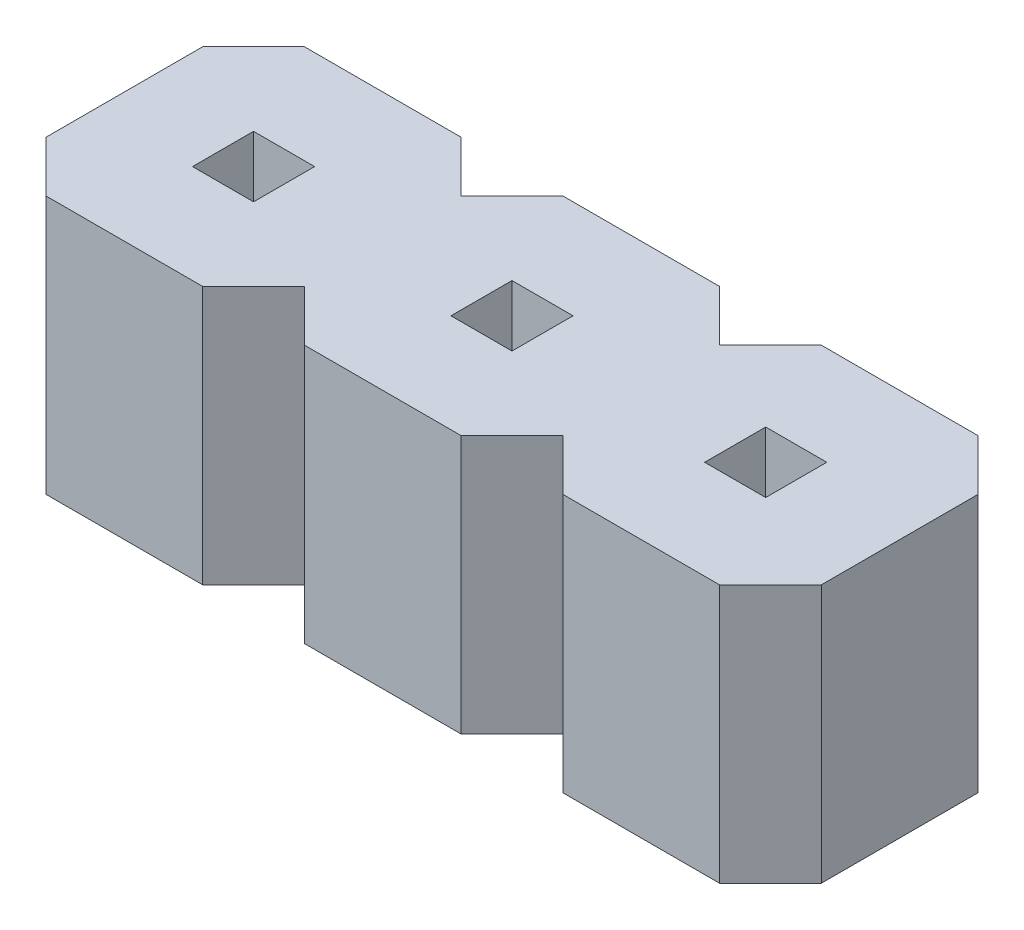
SolidWorks part; units mm, degrees
ref_plane "Спереди" through (0, 0, 0) normal (0, 0, 1) x (1, 0, 0)
ref_plane "Сверху" through (0, 0, 0) normal (0, 1, 0) x (1, 0, 0)
ref_plane "Справа" through (0, 0, 0) normal (1, 0, 0) x (0, 0, -1)
sketch "Sketch1" plane through (0, 0, 0) normal (0, 1, 0) x (1, 0, 0)
  line L0 (-5.08, 1.27) -> (0, 1.27) construction
  line L1 (-0.5, 0) -> (-2.04, 0)
  line L3 (-0.5, 2.54) -> (-2.04, 2.54)
  line L4 (-5.08, 0.5) -> (-5.08, 2.04)
  line L5 (-4.58, 2.54) -> (-5.08, 2.04)
  line L6 (-4.11, 0.97) -> (-3.51, 0.97)
  line L7 (-4.11, 0.97) -> (-4.11, 1.57)
  line L8 (-4.11, 1.57) -> (-3.51, 1.57)
  line L9 (-3.51, 0.97) -> (-3.51, 1.57)
  line L10 (-4.11, 0.97) -> (-3.51, 1.57) construction
  line L11 (-4.11, 1.57) -> (-3.51, 0.97) construction
  line L12 (-1.57, 0.97) -> (-0.97, 0.97)
  line L13 (-1.57, 0.97) -> (-1.57, 1.57)
  line L14 (-1.57, 1.57) -> (-0.97, 1.57)
  line L15 (-0.97, 0.97) -> (-0.97, 1.57)
  line L16 (-1.57, 0.97) -> (-0.97, 1.57) construction
  line L17 (-1.57, 1.57) -> (-0.97, 0.97) construction
  line L18 (-4.58, 0) -> (-5.08, 0.5)
  line L19 (0, 0.5) -> (-0.5, 0)
  line L20 (0, 2.04) -> (-0.5, 2.54)
  line L21 (-2.54, 2.54) -> (-2.54, 0) construction
  line L22 (-2.54, 0.5) -> (-2.04, 0)
  line L23 (-3.04, 2.54) -> (-2.54, 2.04)
  line L24 (-2.54, 2.04) -> (-2.04, 2.54)
  line L25 (-3.04, 0) -> (-2.54, 0.5)
  line L26 (-3.04, 2.54) -> (-4.58, 2.54)
  line L27 (-3.04, 0) -> (-4.58, 0)
  line L28 (0, 2.04) -> (0.5, 2.54)
  line L29 (0.5, 2.54) -> (2.04, 2.54)
  line L30 (2.04, 2.54) -> (2.54, 2.04)
  line L31 (2.54, 2.04) -> (2.54, 0.5)
  line L32 (2.54, 0.5) -> (2.04, 0)
  line L33 (2.04, 0) -> (0.5, 0)
  line L34 (0.5, 0) -> (0, 0.5)
  line L36 (0.9236, 0.97) -> (1.5236, 0.97)
  line L37 (0.9236, 0.97) -> (0.9236, 1.57)
  line L38 (0.9236, 1.57) -> (1.5236, 1.57)
  line L39 (1.5236, 0.97) -> (1.5236, 1.57)
  line L40 (0.9236, 0.97) -> (1.5236, 1.57) construction
  line L41 (0.9236, 1.57) -> (1.5236, 0.97) construction
  point P0 (0, 0)
  point P1 (-5.08, 2.54)
  point P2 (0, 2.54)
  point P3 (-5.08, 0)
  point P7 (-3.81, 1.27)
  point P12 (-1.27, 1.27)
  point P38 (1.2236, 1.27)
  dimension "D1" = 0.6
  dimension "D2" = 0.6
  dimension "D3" = 0.6
  dimension "D4" = 0.6
  dimension "D5" = 2.54
  dimension "D6" = 2.54
  dimension "D7" = 5.08
  dimension "D9" = 1
  dimension "D10" = 0.5
  dimension "D15" = 0.5
  dimension "D16" = 1.54
  dimension "D17" = 0.6
  dimension "D18" = 0.6
  dimension "D19" = 1.54
  dimension "D20" = 0.5
  dimension "D21" = 0.5
  dimension "D22" = 0.5
  dimension "D23" = 0.5
  dimension "D24" = 1.54
extrude "Boss-Extrude1" add sketch "Sketch1" along normal blind 2.54
